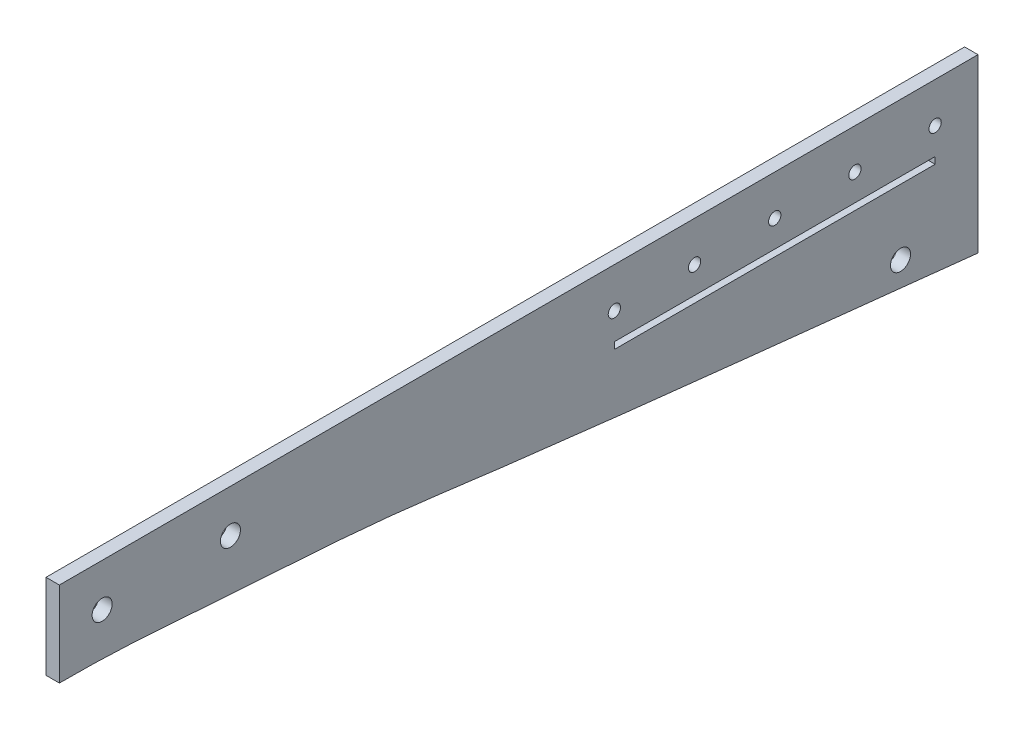
SolidWorks part; units mm, degrees
ref_plane "Front Plane" through (0, 0, 0) normal (0, 0, 1) x (1, 0, 0)
ref_plane "Top Plane" through (0, 0, 0) normal (0, 1, 0) x (1, 0, 0)
ref_plane "Right Plane" through (0, 0, 0) normal (1, 0, 0) x (0, 0, -1)
sketch "Sketch1" plane through (0, 0, -187.325) normal (-1, 0, 0) x (0, 0, 1)
  line L0 (104.7098, 63.5) -> (-113.533, 63.5)
  line L1 (-113.533, 63.5) -> (-113.533, 22.6836)
  line L2 (-65.2457, 47.625) -> (-65.2457, 46.0375) construction
  line L3 (-103.3457, 47.625) -> (-27.1457, 47.625)
  line L4 (53.9098, 63.5) -> (247.0307, 63.5) construction
  line L7 (-103.3457, 47.625) -> (-103.3457, 46.0375)
  line L8 (-103.3457, 46.0375) -> (-27.1457, 46.0375)
  line L9 (-27.1457, 47.625) -> (-27.1457, 46.0375)
  line L10 (-103.3457, 46.8313) -> (-27.1457, 46.8313) construction
  line L11 (104.7098, 60.96) -> (104.7098, 45.8341) construction
  line L12 (56.4498, 63.5) -> (102.1698, 63.5) construction
  line L14 (525.3043, 16.4879) -> (525.3043, 63.5) construction
  line L15 (-27.1457, 53.975) -> (-103.3457, 53.975) construction
  line L16 (-113.533, 22.653) -> (-113.533, 35.56) construction
  line L20 (-65.2457, 63.5) -> (-65.2457, 27.8342) construction
  line L45 (104.7098, 43.3229) -> (104.7098, 63.5)
  circle A0 centre (-84.2957, 53.975) radius 1.4605
  circle A1 centre (-46.1957, 53.975) radius 1.4605
  arc A3 (533.6238, 9.4465) -> (535.4437, 20.4865) centre (531.5697, 15.4551) ccw construction
  circle A5 centre (64.0698, 53.34) radius 3.175 construction
  circle A6 centre (-27.1457, 53.975) radius 1.4605
  circle A7 centre (64.0698, 53.34) radius 2.3813
  circle A8 centre (94.5498, 53.34) radius 2.3813
  circle A10 centre (-103.3457, 53.975) radius 1.4605
  circle A11 centre (-95.118, 30.48) radius 2.3813
  circle A12 centre (-65.2457, 53.975) radius 1.4605
  circle A13 centre (94.5498, 53.34) radius 3.175 construction
  circle A16 centre (-95.118, 30.48) radius 3.175 construction
  spline S1 degree 3 poles (-40644.5689, -9323.1153) (-1.2787, -1443.015) (449.9921, -105.7419) (188.2713, 30.2941) (169.9035, 34.7665) (146.43, 39.591) (116.2055, 43.8548) (90.9874, 43.3112) (59.0669, 40.7341) (33.2874, 39.5878) (-16.4465, 32.8482) (-828.7307, -50.4122) (147.4142, -12.0565) (-41917.1262, -4082.4283) knots -2.092959 -2.092959 -2.092959 -2.092959 0.039495 0.07582 0.117566 0.181239 0.256866 0.346598 0.372017 0.495605 0.537891 0.752596 4.383248 4.383248 4.383248 4.383248 only from (206.7687, 19.4182) to (-132.4717, 20.6251) construction
  spline S2 degree 3 poles (104.7098, 43.3229) (97.2924, 43.3692) (86.4856, 42.9477) (59.0669, 40.7341) (33.2874, 39.5878) (-16.4465, 32.8482) (-71.701, 27.1846) (-112.18, 22.8294) (-113.533, 22.6836) knots 0.290535 0.290535 0.290535 0.290535 0.346598 0.372017 0.495605 0.537891 0.752596 0.760057 0.760057 0.760057 0.760057
  dimension "D7" = 38.1
  dimension "D10" = 4.7625
  dimension "D11" = 2.921
  dimension "D12" = 2.921
  dimension "D13" = 4.7625
  dimension "D14" = 4.7625
  dimension "D17" = 2.921
  dimension "D8" = 2.921
  dimension "D9" = 2.921
  dimension "D3" = 38.1
  dimension "D4" = 1.5875
  dimension "D5" = 590.55
  dimension "D6" = 15.875
  dimension "D15" = 38.1
  dimension "D16" = 9.525
  dimension "D18" = 38.1
  dimension "D19" = 19.05
  dimension "D20" = 19.05
  dimension "D21" = 47.0121
extrude "Boss-Extrude1" add sketch "Sketch1" along normal blind 3.175
equation "\"D8@Sketch1\"=\"D11@Sketch1\""
equation "\"D17@Sketch1\"=\"D11@Sketch1\""
equation "\"D9@Sketch1\"=\"D11@Sketch1\""
equation "\"D12@Sketch1\"=\"D11@Sketch1\""
